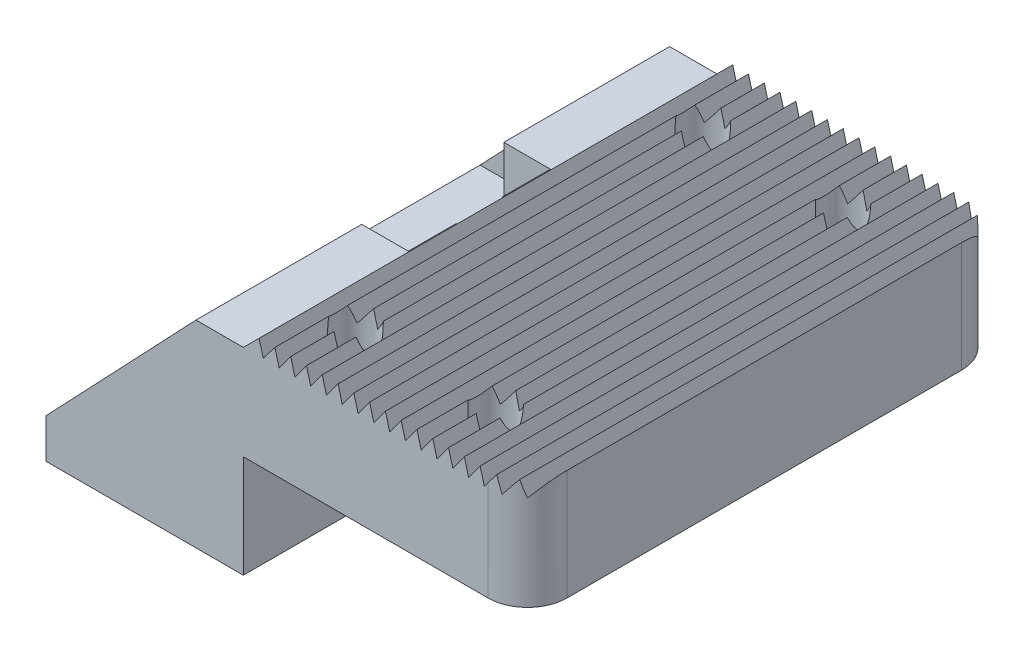
SolidWorks part; units mm, degrees
ref_plane "前视基准面" through (0, 0, 0) normal (0, 0, 1) x (1, 0, 0)
ref_plane "上视基准面" through (0, 0, 0) normal (0, 1, 0) x (1, 0, 0)
ref_plane "右视基准面" through (0, 0, 0) normal (1, 0, 0) x (0, 0, -1)
other "Configuration Table"
sketch "草图1" plane through (0, 0, 0) normal (0, 0, 1) x (1, 0, 0)
  line L0 (0, -11) -> (0, 11)
  line L1 (5.023, 0) -> (-5.9724, 0) construction
  line L2 (0, 11) -> (42, 11)
  line L3 (0, -11) -> (42, -11)
  line L4 (42, 11) -> (42, -11)
  line L5 (0, 9) -> (0, 13)
  line L6 (0, 13) -> (6, 13)
  line L7 (6, 13) -> (8, 11)
  line L8 (8, 11) -> (8.5176, 12.9319)
  line L9 (8.5176, 12.9319) -> (10, 11)
  line L10 (10, 11) -> (10.5359, 13)
  line L11 (10.5359, 13) -> (12, 11)
  line L12 (12, 11) -> (12.5359, 13)
  line L13 (12.5359, 13) -> (14, 11)
  line L14 (14, 11) -> (14.5359, 13)
  line L15 (14.5359, 13) -> (16, 11)
  line L16 (16, 11) -> (16.5359, 13)
  line L17 (16.5359, 13) -> (18, 11)
  line L18 (18, 11) -> (18.5359, 13)
  line L19 (18.5359, 13) -> (20, 11)
  line L20 (20, 11) -> (20.5359, 13)
  line L21 (20.5359, 13) -> (22, 11)
  line L22 (22, 11) -> (22.5359, 13)
  line L23 (22.5359, 13) -> (24, 11)
  line L24 (24, 11) -> (24.5359, 13)
  line L25 (24.5359, 13) -> (26, 11)
  line L26 (26, 11) -> (26.5359, 13)
  line L27 (26.5359, 13) -> (28, 11)
  line L28 (28, 11) -> (28.5359, 13)
  line L29 (28.5359, 13) -> (30, 11)
  line L30 (0, 13) -> (0, 11)
  line L31 (30, 11) -> (0, 11)
  line L32 (30, 11) -> (30.5359, 13)
  line L33 (30.5359, 13) -> (32, 11)
  line L34 (32, 11) -> (32.5359, 13)
  line L35 (32.5359, 13) -> (34, 11)
  line L36 (34, 11) -> (34.5359, 13)
  line L37 (34.5359, 13) -> (36, 11)
  line L38 (36, 11) -> (36.5359, 13)
  line L39 (36.5359, 13) -> (38, 11)
  line L40 (38, 11) -> (38.5359, 13)
  line L41 (38.5359, 13) -> (40, 11)
  line L42 (40, 11) -> (40.5359, 13)
  line L43 (40.5359, 13) -> (42, 11)
  line L44 (40.5359, 9) -> (42, 11)
  line L45 (40, 11) -> (40.5359, 9)
  line L46 (38.5359, 9) -> (40, 11)
  line L47 (38, 11) -> (38.5359, 9)
  line L48 (36.5359, 9) -> (38, 11)
  line L49 (36, 11) -> (36.5359, 9)
  line L50 (34.5359, 9) -> (36, 11)
  line L51 (34, 11) -> (34.5359, 9)
  line L52 (32.5359, 9) -> (34, 11)
  line L53 (32, 11) -> (32.5359, 9)
  line L54 (30.5359, 9) -> (32, 11)
  line L55 (30, 11) -> (30.5359, 9)
  line L56 (28.5359, 9) -> (30, 11)
  line L57 (28, 11) -> (28.5359, 9)
  line L58 (26.5359, 9) -> (28, 11)
  line L59 (26, 11) -> (26.5359, 9)
  line L60 (24.5359, 9) -> (26, 11)
  line L61 (24, 11) -> (24.5359, 9)
  line L62 (22.5359, 9) -> (24, 11)
  line L63 (22, 11) -> (22.5359, 9)
  line L64 (20.5359, 9) -> (22, 11)
  line L65 (20, 11) -> (20.5359, 9)
  line L66 (18.5359, 9) -> (20, 11)
  line L67 (18, 11) -> (18.5359, 9)
  line L68 (16.5359, 9) -> (18, 11)
  line L69 (16, 11) -> (16.5359, 9)
  line L70 (14.5359, 9) -> (16, 11)
  line L71 (14, 11) -> (14.5359, 9)
  line L72 (12.5359, 9) -> (14, 11)
  line L73 (12, 11) -> (12.5359, 9)
  line L74 (10.5359, 9) -> (12, 11)
  line L75 (10, 11) -> (10.5359, 9)
  line L76 (8.5176, 9.0681) -> (10, 11)
  line L77 (8, 11) -> (8.5176, 9.0681)
  line L78 (6, 9) -> (8, 11)
  line L79 (0, 9) -> (6, 9)
  point P6 (0, 0)
  dimension "D2" = 42
  dimension "D3" = 2
  dimension "D4" = 6
  dimension "D5" = 75
  dimension "D6" = 2
  dimension "D7" = 2
  dimension "D8" = 2
  dimension "D9" = 75
  dimension "D10" = 2
  dimension "D11" = 2
  dimension "D12" = 75
  dimension "D13" = 2
  dimension "D14" = 75
  dimension "D15" = 2
  dimension "D16" = 75
  dimension "D17" = 2
  dimension "D18" = 2
  dimension "D19" = 75
  dimension "D20" = 2
  dimension "D21" = 75
  dimension "D22" = 2
  dimension "D23" = 75
  dimension "D24" = 2
  dimension "D25" = 75
  dimension "D26" = 75
  dimension "D27" = 2
  dimension "D28" = 75
  dimension "D29" = 2
  dimension "D30" = 75
  dimension "D31" = 2
  dimension "D32" = 2
  dimension "D33" = 75
  dimension "D34" = 2
  dimension "D35" = 75
  dimension "D36" = 2
  dimension "D37" = 2
  dimension "D38" = 2
  dimension "D39" = 75
  dimension "D40" = 22
extrude "凸台-拉伸1" add sketch "草图1" along normal blind 60
fillet "圆角1" radius 5 2 edges at (42, 0, 0) (42, 0, 60)
sketch "草图3" plane through (0, -11, 0) normal (0, -1, 0) x (1, 0, 0)
  line L0 (37, 60) -> (37, 0) construction
  line L1 (0, 0) -> (37, 0) construction
  line L2 (0, 30) -> (37, 30) construction
  line L4 (12.2, 60) -> (12.2, 0)
  line L5 (0, 60) -> (37, 60) construction
  line L6 (18.5, 30) -> (18.5, 60) construction
  line L7 (0, 60) -> (0, 0) construction
  circle A0 centre (12.2, 52) radius 2.5
  circle A1 centre (12.2, 8) radius 2.5
  circle A2 centre (30, 8) radius 2.5
  circle A3 centre (30, 52) radius 2.5
  dimension "D2" = 5
  dimension "D1" = 12.2
  dimension "D3" = 8
  dimension "D4" = 7
extrude "切除-拉伸2" cut sketch "草图3" against normal through all contours A2 | L4 A0 | A1 L4 | A1 L4 | L4 A0 | A3
sketch "草图5" plane through (0, 0, 0) normal (-1, 0, 0) x (0, 0, 1)
  line L0 (30, 9) -> (30, -11) construction
  line L1 (60, 9) -> (0, 9) construction
  line L2 (60, -11) -> (0, -11) construction
  line L3 (27.05, 9) -> (32.95, 9)
  line L4 (60, 9) -> (0, 9) construction
  line L5 (60, 9) -> (0, 9) construction
  arc A0 (27.05, 9) -> (32.95, 9) centre (30, 9) ccw
  point P11 (14, 9)
  dimension "D1" = 2.95
  dimension "D2" = 16
extrude "切除-拉伸4" cut sketch "草图5" against normal blind 6
sketch "草图6" plane through (0, 0, 0) normal (-1, 0, 0) x (0, 0, 1)
  line L0 (21, 9) -> (39, 9)
  line L1 (32.95, 9) -> (27.05, 9) construction
  line L2 (60, 9) -> (32.95, 9) construction
  line L3 (39, 9) -> (39, -11)
  line L4 (60, -11) -> (0, -11) construction
  line L5 (39, -11) -> (21, -11)
  line L6 (30, 9) -> (30, -11) construction
  line L7 (21, 9) -> (21, -11)
  dimension "D1" = 9
extrude "切除-拉伸5" cut sketch "草图6" against normal blind 5.9
sketch "草图7" plane through (0, -11, 0) normal (0, -1, 0) x (1, 0, 0)
  line L0 (37, 60) -> (-19, 60)
  line L1 (-19, 60) -> (-19, 0)
  line L2 (-19, 0) -> (37, 0)
  line L3 (0, 60) -> (0, 39) construction
  line L4 (5.9, 30) -> (42, 30) construction
  line L5 (5.9, 21) -> (5.9, 39) construction
  line L6 (6, 60) -> (6, 0)
  line L7 (0, 60) -> (0, 39)
  line L8 (0, 60) -> (0, 39)
  line L9 (0, 39) -> (5.9, 39)
  line L10 (5.9, 39) -> (5.9, 21)
  line L11 (5.9, 21) -> (0, 21)
  line L12 (0, 21) -> (0, 0)
  line L13 (0, 0) -> (37, 0)
  line L14 (42, 5) -> (42, 55)
  line L15 (37, 60) -> (0, 60)
  line L21 (0, 0) -> (37, 0)
  line L22 (42, 5) -> (42, 55)
  line L23 (37, 60) -> (0, 60)
  line L24 (0, 39) -> (5.9, 39)
  line L25 (5.9, 39) -> (5.9, 21)
  line L26 (5.9, 21) -> (0, 21)
  line L27 (0, 21) -> (0, 0)
  circle A0 centre (-7, 46) radius 2.5
  circle A1 centre (-7, 14) radius 2.5
  arc A2 (37, 0) -> (42, 5) centre (37, 5) ccw
  arc A3 (42, 55) -> (37, 60) centre (37, 55) ccw
  arc A4 (37, 0) -> (42, 5) centre (37, 5) ccw
  arc A5 (42, 55) -> (37, 60) centre (37, 55) ccw
  line M16 (0, 60) -> (0, 39)
  line M17 (0, 39) -> (5.9, 39)
  line M18 (5.9, 39) -> (5.9, 21)
  line M19 (5.9, 21) -> (0, 21)
  line M20 (0, 21) -> (0, 0)
  line M21 (0, 0) -> (37, 0)
  dimension "D5" = 5
  dimension "D2" = 19
  dimension "D3" = 32
  dimension "D4" = 7
  dimension "D6" = 6
  dimension "D1" = 0
extrude "凸台-拉伸2" add sketch "草图7" along normal blind 5 separate body contours L1 L2 L0 A0 A1 M20 M19 M18 M17 M16 | L4 L6 L0 M18 M16 M17 | L4 L25 L6 M19 M20 M21
sketch "草图8" plane through (0, -11, 0) normal (0, -1, 0) x (1, 0, 0)
  line L0 (6, 60) -> (6, 0)
  line L1 (6, 60) -> (37, 60)
  line L2 (37, 0) -> (6, 0)
  line L8 (0, 60) -> (0, 39)
  line L9 (0, 39) -> (5.9, 39)
  line L10 (5.9, 39) -> (5.9, 21)
  line L11 (5.9, 21) -> (0, 21)
  line L12 (0, 21) -> (0, 0)
  line L13 (0, 0) -> (37, 0)
  line L14 (42, 5) -> (42, 55)
  line L15 (37, 60) -> (0, 60)
  line L22 (42, 5) -> (42, 55)
  arc A2 (37, 0) -> (42, 5) centre (37, 5) ccw
  arc A3 (42, 55) -> (37, 60) centre (37, 55) ccw
  arc A4 (37, 0) -> (42, 5) centre (37, 5) ccw
  arc A5 (42, 55) -> (37, 60) centre (37, 55) ccw
  dimension "D1" = 0
extrude "切除-拉伸6" cut sketch "草图8" against normal blind 8
sketch "草图9" plane through (0, 0, 60) normal (0, 0, 1) x (1, 0, 0)
  line L0 (0, 9) -> (-19, -11)
  line L1 (-19, -11) -> (0, -11)
  line L2 (0, -11) -> (0, 9)
extrude "凸台-拉伸3" add sketch "草图9" against normal blind 5
sketch "草图10" plane through (0, 0, 0) normal (0, 0, -1) x (-1, 0, 0)
  line L0 (0, 9) -> (0, -11)
  line L1 (0, -11) -> (19, -11)
  line L2 (19, -11) -> (0, 9)
extrude "凸台-拉伸4" add sketch "草图10" against normal blind 5
sketch "草图11" plane through (0, 0, 60) normal (0, 0, 1) x (1, 0, 0)
  line L0 (6, -3) -> (6, -16)
  line L1 (6, -16) -> (37, -3)
  line L2 (37, -3) -> (6, -3)
extrude "凸台-拉伸5" add sketch "草图11" against normal blind 45
sketch "草图12" plane through (0, 0, 60) normal (0, 0, 1) x (1, 0, 0)
  line L0 (37, -3) -> (6, -3)
  line L1 (6, -3) -> (6, -16)
  line L2 (37, -3) -> (6, -16)
extrude "切除-拉伸7" cut sketch "草图12" against normal blind 15
